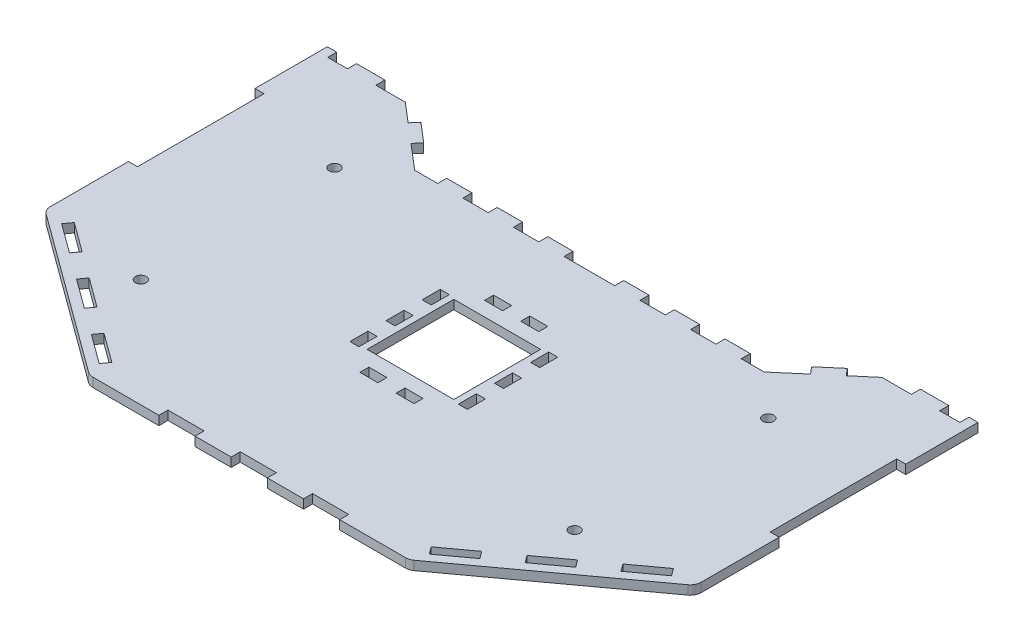
SolidWorks part; units mm, degrees
material "Beech"
ref_plane "Front" through (0, 0, 0) normal (0, 0, 1) x (1, 0, 0)
ref_plane "Top" through (0, 0, 0) normal (0, 1, 0) x (1, 0, 0)
ref_plane "Right" through (0, 0, 0) normal (1, 0, 0) x (0, 0, -1)
sketch "Sketch1" plane through (0, 0, 0) normal (0, 1, 0) x (1, 0, 0)
  line L0 (47.4037, 85) -> (-47.4037, 85) construction
  line L3 (-90, 100) -> (90, 100) construction
  line L5 (0, -9.0806) -> (0, 7.6411) construction
  line L6 (13.75, 52.5) -> (16.25, 52.5)
  line L7 (-47.4037, 85) -> (-64.159, 99.2831) construction
  line L8 (-66.1052, 100) -> (-90, 100) construction
  line L9 (-90, 100) -> (-90, 25)
  line L15 (16.25, 57.5) -> (16.25, 52.5)
  line L19 (90, 25) -> (40, -11.5806) construction
  line L20 (90, 100) -> (90, 25)
  line L21 (66.1052, 100) -> (90, 100) construction
  line L22 (47.4037, 85) -> (64.159, 99.2831) construction
  line L23 (2.5, 63.5) -> (7.5, 63.5)
  line L28 (-40, -11.5806) -> (-25, -11.5806)
  line L29 (-12, 33) -> (12, 33)
  line L30 (-15, 27.75) -> (15, 27.75) construction
  line L31 (-15, 27.75) -> (-15, 62.25) construction
  line L32 (-15, 62.25) -> (15, 62.25) construction
  line L33 (15, 27.75) -> (15, 62.25) construction
  line L34 (-15, 27.75) -> (15, 62.25) construction
  line L35 (-15, 62.25) -> (15, 27.75) construction
  line L36 (-7.5, 61) -> (-2.5, 61)
  line L37 (-7.5, 61) -> (-7.5, 63.5)
  line L38 (-7.5, 63.5) -> (-2.5, 63.5)
  line L39 (-2.5, 61) -> (-2.5, 63.5)
  line L40 (-7.5, 61) -> (-2.5, 63.5) construction
  line L41 (-7.5, 63.5) -> (-2.5, 61) construction
  line L42 (7.5, 61) -> (7.5, 63.5)
  line L43 (2.5, 61) -> (7.5, 61)
  line L44 (2.5, 61) -> (2.5, 63.5)
  line L53 (15.2531, 45) -> (4.1057, 45) construction
  line L62 (-7.5, 26.5) -> (-2.5, 26.5)
  line L63 (-2.5, 29) -> (-2.5, 26.5)
  line L64 (-7.5, 29) -> (-2.5, 29)
  line L65 (-7.5, 29) -> (-7.5, 26.5)
  line L66 (2.5, 29) -> (2.5, 26.5)
  line L67 (2.5, 29) -> (7.5, 29)
  line L68 (7.5, 29) -> (7.5, 26.5)
  line L69 (2.5, 26.5) -> (7.5, 26.5)
  line L70 (-16.25, 47.5) -> (-16.25, 42.5)
  line L71 (-13.75, 57.5) -> (-16.25, 57.5)
  line L72 (-13.75, 57.5) -> (-13.75, 52.5)
  line L73 (-13.75, 52.5) -> (-16.25, 52.5)
  line L74 (-16.25, 57.5) -> (-16.25, 52.5)
  line L75 (-13.75, 57.5) -> (-16.25, 52.5) construction
  line L76 (-13.75, 52.5) -> (-16.25, 57.5) construction
  line L77 (-13.75, 42.5) -> (-16.25, 42.5)
  line L78 (-13.75, 47.5) -> (-13.75, 42.5)
  line L79 (-13.75, 47.5) -> (-16.25, 47.5)
  line L80 (-16.25, 37.5) -> (-16.25, 32.5)
  line L81 (-13.75, 32.5) -> (-16.25, 32.5)
  line L82 (-13.75, 37.5) -> (-13.75, 32.5)
  line L83 (-13.75, 37.5) -> (-16.25, 37.5)
  line L105 (90, 80) -> (87.5, 80)
  line L106 (90, 80) -> (90, 45)
  line L107 (90, 45) -> (87.5, 45)
  line L108 (87.5, 80) -> (87.5, 45)
  line L109 (90, 80) -> (87.5, 45) construction
  line L110 (90, 45) -> (87.5, 80) construction
  line L114 (-40, -11.5806) -> (40, -11.5806) construction
  line L115 (13.75, 57.5) -> (16.25, 57.5)
  line L116 (13.75, 57.5) -> (13.75, 52.5)
  line L117 (13.75, 47.5) -> (16.25, 47.5)
  line L118 (13.75, 47.5) -> (13.75, 42.5)
  line L119 (13.75, 42.5) -> (16.25, 42.5)
  line L120 (16.25, 47.5) -> (16.25, 42.5)
  line L121 (13.75, 37.5) -> (16.25, 37.5)
  line L122 (13.75, 37.5) -> (13.75, 32.5)
  line L123 (13.75, 32.5) -> (16.25, 32.5)
  line L124 (16.25, 37.5) -> (16.25, 32.5)
  line L129 (-90, 80) -> (-87.5, 80)
  line L130 (-90, 80) -> (-90, 45)
  line L131 (-90, 45) -> (-87.5, 45)
  line L132 (-87.5, 80) -> (-87.5, 45)
  line L133 (22.5, 63.5) -> (27.5, 63.5) [skipped]
  line L134 (27.5, 61) -> (27.5, 63.5) [skipped]
  line L135 (22.5, 61) -> (27.5, 61) [skipped]
  line L136 (22.5, 61) -> (22.5, 63.5) [skipped]
  line L137 (12.5, 63.5) -> (17.5, 63.5) [skipped]
  line L138 (17.5, 61) -> (17.5, 63.5) [skipped]
  line L139 (12.5, 61) -> (17.5, 61) [skipped]
  line L140 (12.5, 61) -> (12.5, 63.5) [skipped]
  line L141 (-16.25, 27.5) -> (-16.25, 22.5) [skipped]
  line L142 (-13.75, 22.5) -> (-16.25, 22.5) [skipped]
  line L143 (-13.75, 27.5) -> (-13.75, 22.5) [skipped]
  line L144 (-13.75, 27.5) -> (-16.25, 27.5) [skipped]
  line L145 (-12, 33) -> (-12, 57)
  line L146 (-12, 57) -> (12, 57)
  line L147 (12, 33) -> (12, 57)
  line L148 (-12, 33) -> (12, 57) construction
  line L149 (-12, 57) -> (12, 33) construction
  line L150 (-25, -11.5806) -> (-25, -9.0806)
  line L151 (-25, -9.0806) -> (-15, -9.0806)
  line L152 (-15, -9.0806) -> (-15, -11.5806)
  line L153 (-15, -11.5806) -> (-5, -11.5806)
  line L154 (-5, -11.5806) -> (-5, -9.0806)
  line L155 (-5, -9.0806) -> (5, -9.0806)
  line L156 (5, -9.0806) -> (5, -11.5806)
  line L157 (5, -11.5806) -> (15, -11.5806)
  line L158 (15, -11.5806) -> (15, -9.0806)
  line L159 (15, -9.0806) -> (25, -9.0806)
  line L160 (25, -9.0806) -> (25, -11.5806)
  line L161 (25, -11.5806) -> (40, -11.5806)
  line L162 (-87.4, 97.5) -> (-81.9, 97.5)
  line L163 (-81.9, 97.5) -> (-81.9, 100)
  line L164 (-81.9, 100) -> (-74.0673, 100)
  line L165 (45, -9.0806) -> (45, 7.6411) construction
  line L166 (-74.0673, 100) -> (-74.0673, 97.5)
  line L167 (-74.0673, 97.5) -> (-62.0673, 97.5) construction
  line L168 (87.5, 97.5) -> (81.9, 97.5)
  line L169 (81.9, 97.5) -> (81.9, 100)
  line L170 (81.9, 100) -> (74.0673, 100)
  line L171 (74.0673, 100) -> (74.0673, 97.5)
  line L172 (74.0673, 97.5) -> (62.0673, 97.5) construction
  line L173 (62.0673, 97.5) -> (47.4037, 85) construction
  line L174 (-90, 100) -> (-87.4, 100)
  line L175 (-87.4, 100) -> (-87.4, 97.5)
  line L176 (87.5, 97.5) -> (87.5, 100)
  line L177 (87.5, 100) -> (90, 100)
  line L178 (-65.921, 97.5) -> (-48.3247, 82.5) construction
  line L179 (-48.3247, 82.5) -> (48.3247, 82.5) construction
  line L180 (48.3247, 82.5) -> (65.921, 97.5) construction
  line L181 (-65.921, 97.5) -> (-74.0673, 97.5)
  line L182 (65.921, 97.5) -> (74.0673, 97.5)
  line L183 (-65.921, 97.5) -> (-60.5938, 92.9589)
  line L184 (-60.5938, 92.9589) -> (-58.972, 94.8614)
  line L185 (-58.972, 94.8614) -> (-53.6449, 90.3203)
  line L186 (-53.6449, 90.3203) -> (-55.2667, 88.4178)
  line L187 (-55.2667, 88.4178) -> (-48.3247, 82.5)
  line L188 (-48.3247, 82.5) -> (-42, 82.5)
  line L189 (-42, 82.5) -> (-42, 85)
  line L190 (-42, 85) -> (-35, 85)
  line L191 (-35, 85) -> (-35, 82.5)
  line L192 (-35, 82.5) -> (-28, 82.5)
  line L193 (-28, 82.5) -> (-28, 85)
  line L194 (-28, 85) -> (-21, 85)
  line L195 (-21, 85) -> (-21, 82.5)
  line L196 (-21, 82.5) -> (-14, 82.5)
  line L197 (-14, 82.5) -> (-14, 85)
  line L198 (-14, 85) -> (-7, 85)
  line L199 (-7, 85) -> (-7, 82.5)
  line L200 (-7, 82.5) -> (0, 82.5)
  line L201 (0, 82.5) -> (7, 82.5)
  line L202 (7, 82.5) -> (7, 85)
  line L203 (7, 85) -> (14, 85)
  line L204 (14, 85) -> (14, 82.5)
  line L205 (14, 82.5) -> (21, 82.5)
  line L206 (21, 82.5) -> (21, 85)
  line L207 (21, 85) -> (28, 85)
  line L208 (28, 85) -> (28, 82.5)
  line L209 (28, 82.5) -> (35, 82.5)
  line L210 (35, 82.5) -> (35, 85)
  line L211 (35, 85) -> (42, 85)
  line L212 (42, 85) -> (42, 82.5)
  line L213 (42, 82.5) -> (48.3247, 82.5)
  line L214 (65.921, 97.5) -> (60.5938, 92.9589)
  line L215 (60.5938, 92.9589) -> (58.972, 94.8614)
  line L216 (58.972, 94.8614) -> (53.6449, 90.3203)
  line L217 (53.6449, 90.3203) -> (55.2667, 88.4178)
  line L218 (55.2667, 88.4178) -> (48.3247, 82.5)
  line L219 (40, -11.5806) -> (44.234, -11.5806)
  line L220 (44.234, -11.5806) -> (90, 21.9024)
  line L221 (90, 21.9024) -> (90, 25)
  line L222 (90, 28.0976) -> (35.766, -11.5806) construction
  line L223 (45.6495, -7.4474) -> (53.7201, -1.5428)
  line L224 (45.6495, -7.4474) -> (44.1733, -5.4298)
  line L225 (53.7201, -1.5428) -> (52.244, 0.4749)
  line L226 (44.1733, -5.4298) -> (52.244, 0.4749)
  line L227 (52.9821, -0.534) -> (44.9114, -6.4386) construction
  line L228 (49.6848, -4.4951) -> (48.2086, -2.4775) construction
  line L229 (60.9636, 3.7566) -> (69.0342, 9.6612)
  line L230 (69.0342, 9.6612) -> (67.5581, 11.6788)
  line L231 (59.4874, 5.7742) -> (67.5581, 11.6788)
  line L232 (60.9636, 3.7566) -> (59.4874, 5.7742)
  line L233 (76.2776, 14.9606) -> (84.3483, 20.8652)
  line L234 (84.3483, 20.8652) -> (82.8722, 22.8828)
  line L235 (74.8015, 16.9782) -> (82.8722, 22.8828)
  line L236 (76.2776, 14.9606) -> (74.8015, 16.9782)
  line L237 (-49.6848, -4.4951) -> (-48.2086, -2.4775) construction
  line L238 (-52.9821, -0.534) -> (-44.9114, -6.4386) construction
  line L239 (-90, 28.0976) -> (-35.766, -11.5806) construction
  line L240 (-90, 25) -> (-40, -11.5806) construction
  line L241 (-76.2776, 14.9606) -> (-74.8015, 16.9782)
  line L242 (-74.8015, 16.9782) -> (-82.8722, 22.8828)
  line L243 (-84.3483, 20.8652) -> (-82.8722, 22.8828)
  line L244 (-76.2776, 14.9606) -> (-84.3483, 20.8652)
  line L245 (-60.9636, 3.7566) -> (-59.4874, 5.7742)
  line L246 (-59.4874, 5.7742) -> (-67.5581, 11.6788)
  line L247 (-69.0342, 9.6612) -> (-67.5581, 11.6788)
  line L248 (-60.9636, 3.7566) -> (-69.0342, 9.6612)
  line L249 (-44.1733, -5.4298) -> (-52.244, 0.4749)
  line L250 (-53.7201, -1.5428) -> (-52.244, 0.4749)
  line L251 (-45.6495, -7.4474) -> (-44.1733, -5.4298)
  line L252 (-45.6495, -7.4474) -> (-53.7201, -1.5428)
  line L253 (-44.234, -11.5806) -> (-90, 21.9024)
  line L254 (-44.234, -11.5806) -> (-40, -11.5806)
  line L255 (-90, 21.9024) -> (-90, 25)
  circle A4 centre (-60, 72) radius 1.5
  circle A5 centre (-60, 18.4194) radius 1.5
  arc A12 (-64.159, 99.2831) -> (-66.1052, 100) centre (-66.1052, 97) ccw construction
  arc A13 (66.1052, 100) -> (64.159, 99.2831) centre (66.1052, 97) ccw construction
  circle A14 centre (60, 18.4194) radius 1.5
  circle A15 centre (60, 72) radius 1.5
  point P0 (0, 0)
  point P22 (0, 85)
  point P28 (0, 45)
  point P34 (0, 45)
  point P54 (-65, 100)
  point P57 (65, 100)
  point P61 (88.75, 62.5)
  point P63 (90, 62.5)
  point P66 (90, 25)
  point P69 (-90, 25)
  point P70 (0, 45)
  point P76 (-5, 62.25)
  point P77 (0, -11.5806)
  point P112 (-15, 57.5)
  point P113 (-15, 55)
  point P224 (48.9467, -3.4863)
  point P228 (-48.9467, -3.4863)
  point P229 (0, 0)
  point P230 (-59.4874, 16.9782)
  point P231 (-59.4874, 18.4194)
  point P232 (42, 14.9606)
  point P233 (0, 0)
  dimension "D12" = 94.8074
  dimension "D14" = 3
  dimension "D15" = 23.8948
  dimension "D16" = 24
  dimension "D30" = 40
  dimension "D13" = 3
  dimension "D33" = 80
  dimension "D54" = 30
  dimension "D5" = 75
  dimension "D6" = 111.5806
  dimension "D7" = 11.5806
  dimension "D8" = 15
  dimension "D9" = 25
  dimension "D10" = 42.5963
  dimension "D11" = 23.8948
  dimension "D17" = 24
  dimension "D18" = 34.5
  dimension "D19" = 30
  dimension "D20" = 2.5
  dimension "D21" = 5
  dimension "D22" = 7.5
  dimension "D23" = 4
  dimension "D24" = 5
  dimension "D25" = 2.5
  dimension "D26" = 5
  dimension "D27" = 4.75
  dimension "D29" = 5
  dimension "D31" = 2.5
  dimension "D32" = 35
  dimension "D34" = 15
  dimension "D35" = 2.5
  dimension "D36" = 10
  dimension "D38" = 2.5
  dimension "D37" = 10
  dimension "D39" = 12
  dimension "D40" = 5.5
  dimension "D41" = 2.5
  dimension "D42" = 2.5
  dimension "D43" = 2.5
  dimension "D44" = 7
  dimension "D45" = 7
  dimension "D46" = 7
  dimension "D47" = 5.6
  dimension "D48" = 2.5
  dimension "D49" = 2.5
  dimension "D50" = 10
  dimension "D51" = 7
  dimension "D53" = 8.975
  dimension "D55" = 28
  dimension "D56" = 30
  dimension "D28" = 4
  dimension "D52" = 3
extrude "Boss-Extrude1" add sketch "Sketch1" along normal blind 2.5
fillet "Fillet1" radius 3 4 edges at (90, 1.25, -21.9024) (44.234, 1.25, 11.5806) (-44.234, 1.25, 11.5806) (-90, 1.25, -21.9024)
